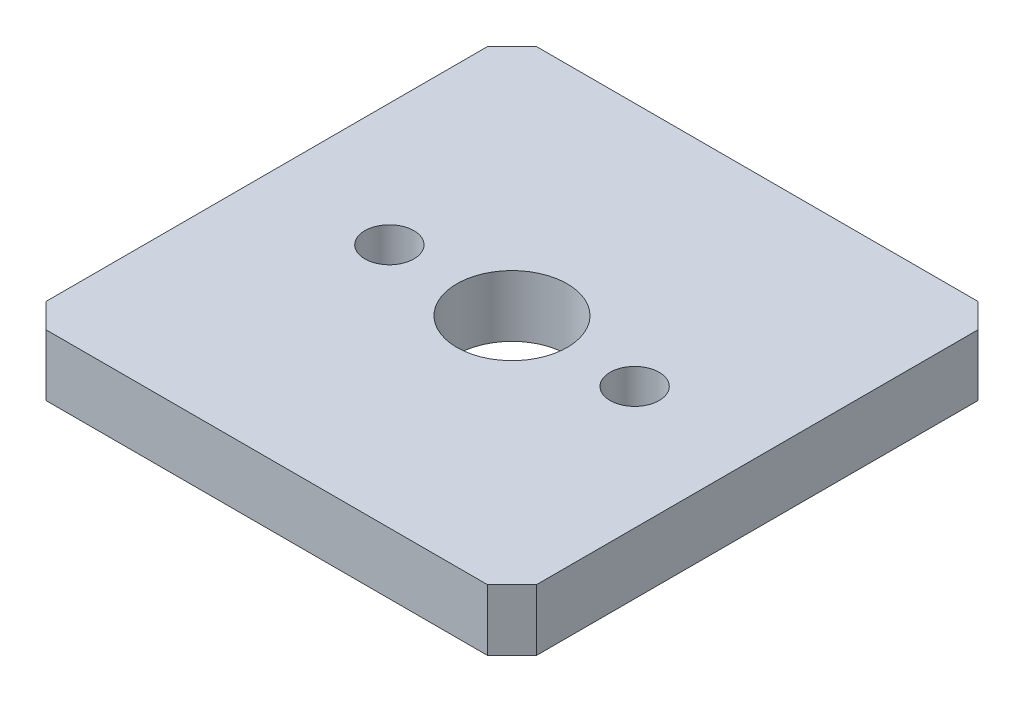
SolidWorks part; units mm, degrees
ref_plane "Front Plane" through (0, 0, 0) normal (0, 0, 1) x (1, 0, 0)
ref_plane "Top Plane" through (0, 0, 0) normal (0, 1, 0) x (1, 0, 0)
ref_plane "Right Plane" through (0, 0, 0) normal (1, 0, 0) x (0, 0, -1)
sketch "Sketch2" plane through (0, 0, 0) normal (0, 1, 0) x (1, 0, 0)
  line L0 (-20, 18) -> (-18, 20)
  line L1 (-18, 20) -> (18, 20)
  line L2 (-20, 18) -> (-20, -18)
  line L3 (-18, -20) -> (18, -20)
  line L4 (20, 18) -> (20, -18)
  line L5 (-20, 20) -> (20, -20) construction
  line L6 (-20, -20) -> (20, 20) construction
  line L7 (18, 20) -> (20, 18)
  line L8 (-20, -18) -> (-18, -20)
  line L9 (18, -20) -> (20, -18)
  circle A0 centre (0, 0) radius 4.5
  circle A1 centre (10, 0) radius 2
  circle A2 centre (-10, 0) radius 2
  dimension "D1" = 9
  dimension "D2" = 4
  dimension "D3" = 4
  dimension "D4" = 10
  dimension "D5" = 10
  dimension "D6" = 40
  dimension "D7" = 40
extrude "Boss-Extrude1" add sketch "Sketch2" along normal blind 5
